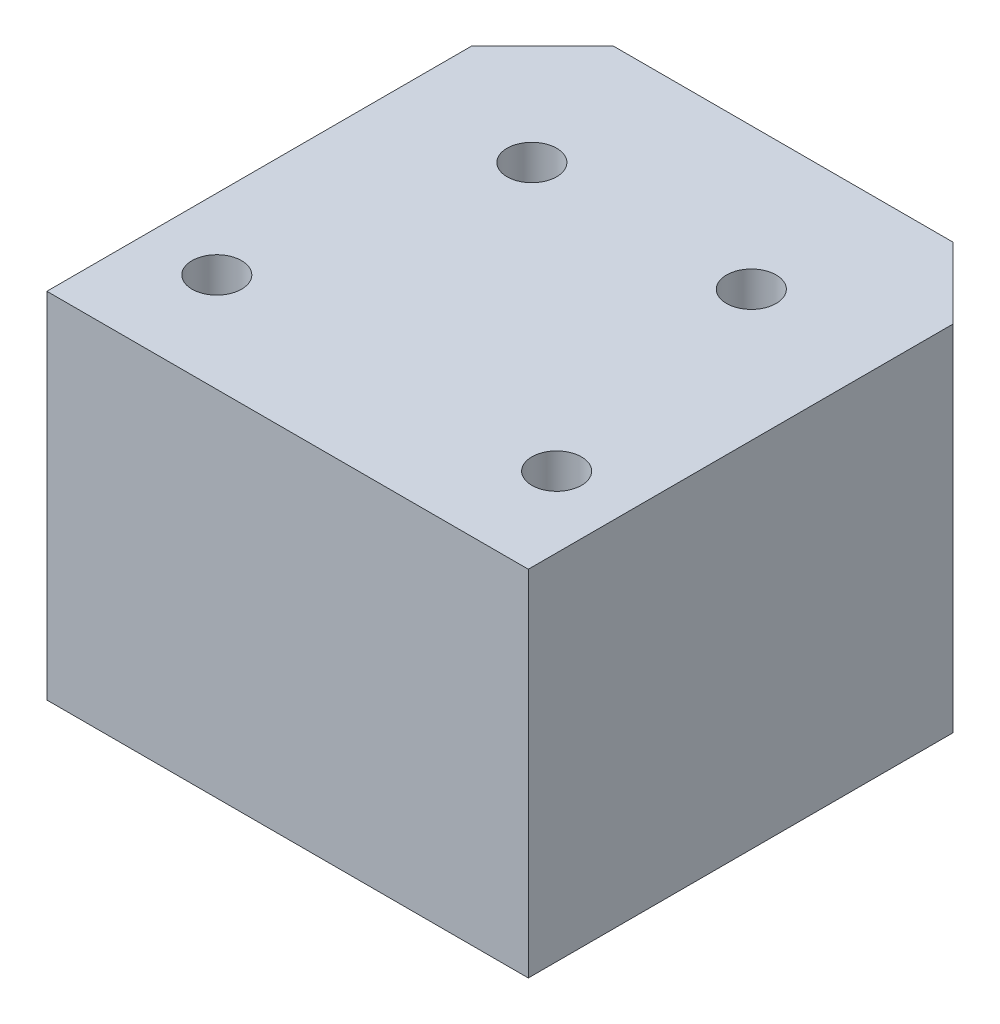
SolidWorks part; units mm, degrees
ref_plane "Спереди" through (0, 0, 0) normal (0, 0, 1) x (1, 0, 0)
ref_plane "Сверху" through (0, 0, 0) normal (0, 1, 0) x (1, 0, 0)
ref_plane "Справа" through (0, 0, 0) normal (1, 0, 0) x (0, 0, -1)
sketch "Sketch1" plane through (0, 0, 0) normal (0, 0, 1) x (1, 0, 0)
  line L0 (-25.6426, 75.5512) -> (-25.6426, 32.5512) construction
  line L1 (8.3574, 41.5512) -> (-25.6426, 41.5512)
  line L2 (8.3574, 41.5512) -> (8.3574, 66.5512)
  line L3 (8.3574, 66.5512) -> (-25.6426, 66.5512)
  line L4 (-25.6426, 41.5512) -> (-25.6426, 66.5512)
  line L5 (8.3574, 41.5512) -> (-25.6426, 66.5512) construction
  line L6 (8.3574, 66.5512) -> (-25.6426, 41.5512) construction
  line L7 (8.3574, 32.5512) -> (8.3574, 75.5512) construction
  line L8 (-25.6426, 54.0512) -> (8.3574, 54.0512) construction
  point P0 (-8.6426, 54.0512)
  point P5 (0, 0)
  point P12 (-25.6426, 54.0512)
  point P13 (0, 0)
  point P14 (-8.6426, 55.1556)
  dimension "D1" = 25
extrude "Extrude1" add sketch "Sketch1" against normal blind 30
sketch "Sketch2" plane through (0, 0, 0) normal (0, 0, 1) x (1, 0, 0)
  line L4 (-25.6426, 66.5512) -> (-25.6426, 41.5512)
  line L5 (-25.6426, 41.5512) -> (8.3574, 41.5512)
  line L6 (8.3574, 41.5512) -> (8.3574, 66.5512)
  line L7 (8.3574, 66.5512) -> (-25.6426, 66.5512)
  line L8 (-25.6426, 66.5512) -> (-25.6426, 41.5512)
  line L9 (-25.6426, 41.5512) -> (8.3574, 41.5512)
  line L10 (8.3574, 41.5512) -> (8.3574, 66.5512)
  line L11 (8.3574, 66.5512) -> (-25.6426, 66.5512)
  dimension "D1" = 0
extrude "Extrude2" add sketch "Sketch2" along normal blind 5
chamfer "Chamfer1" distance 5 angle 45 2 edges at (-25.6426, 54.0512, -30) (8.3574, 54.0512, -30)
sketch "Sketch3" plane through (0, 41.5512, 0) normal (0, -1, 0) x (1, 0, 0)
  line L0 (-8.6426, -30) -> (-8.6426, 5) construction
  line L1 (-20.6426, -30) -> (3.3574, -30) construction
  line L2 (-25.6426, 5) -> (8.3574, 5) construction
  circle A0 centre (-16.3926, -20) radius 1.75
  circle A1 centre (-0.8926, -20) radius 1.75
  circle A2 centre (-20.6426, -2) radius 1.75
  circle A3 centre (3.3574, -2) radius 1.75
  point P12 (3.3574, -2)
  point P25 (0, 0)
  dimension "D3" = 3.5
  dimension "D1" = 15.5
  dimension "D2" = 10
  dimension "D4" = 24
  dimension "D5" = 18
extrude "Cut-Extrude1" cut sketch "Sketch3" against normal through all
